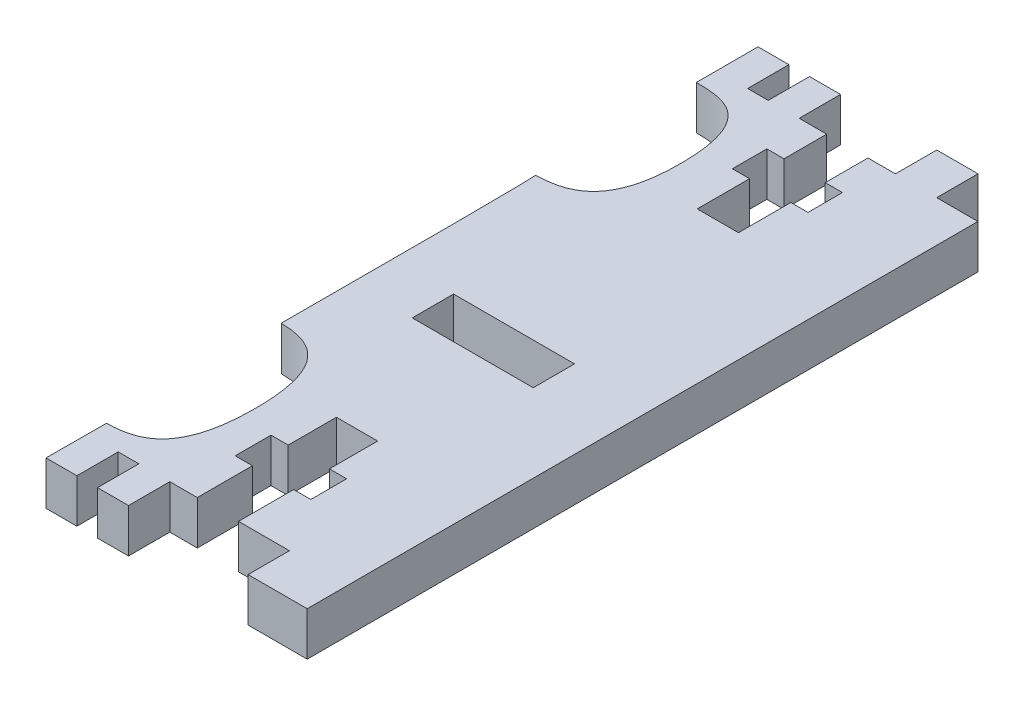
SolidWorks part; units mm, degrees
material "Acrylic (Medium-high impact)"
ref_plane "Front Plane" through (0, 0, 0) normal (0, 0, 1) x (1, 0, 0)
ref_plane "Top Plane" through (0, 0, 0) normal (0, 1, 0) x (1, 0, 0)
ref_plane "Right Plane" through (0, 0, 0) normal (1, 0, 0) x (0, 0, -1)
sketch "Sketch1" plane through (0, 0, 0) normal (0, 1, 0) x (1, 0, 0)
  line L0 (-28.6103, -11.3519) -> (-28.6103, -15.732)
  line L1 (-28.6103, 31.4899) -> (-28.6103, 35.97)
  line L2 (-28.6103, 35.97) -> (-26.3674, 35.97)
  line L3 (-12.6388, 35.97) -> (-12.6388, 32.9698)
  line L4 (-12.6388, 32.9698) -> (-9.6441, 32.9698)
  line L5 (-9.6441, 32.9698) -> (-9.6441, -15.732)
  line L6 (-9.6441, -15.732) -> (-13.9364, -15.732)
  line L7 (-24.1183, 9.369) -> (-24.1183, 6.3689)
  line L8 (-24.1183, 6.3689) -> (-15.3339, 6.3689)
  line L9 (-15.3339, 6.3689) -> (-15.3339, 9.369)
  line L10 (-15.3339, 9.369) -> (-24.1183, 9.369)
  line L11 (-22.6209, -15.732) -> (-22.6209, -12.7318)
  line L12 (-22.6209, -12.7318) -> (-20.6245, -12.7318)
  line L13 (-20.6245, -12.7318) -> (-20.6245, -8.7317)
  line L14 (-20.6245, -8.7317) -> (-21.8722, -8.7317)
  line L15 (-21.8722, -8.7317) -> (-21.8722, -8.6317)
  line L16 (-21.8722, -8.6317) -> (-21.8722, -6.1316)
  line L17 (-21.8722, -6.1316) -> (-20.6245, -6.1316)
  line L18 (-20.6245, -6.1316) -> (-20.6245, -2.6314)
  line L19 (-20.6245, -2.6314) -> (-17.63, -2.6314)
  line L20 (-17.63, -2.6314) -> (-17.63, -6.1316)
  line L21 (-17.63, -6.1316) -> (-16.3822, -6.1316)
  line L22 (-16.3822, -6.1316) -> (-16.3822, -8.6317)
  line L23 (-16.3822, -8.6317) -> (-16.3822, -8.7317)
  line L24 (-16.3822, -8.7317) -> (-17.63, -8.7317)
  line L25 (-17.63, -8.7317) -> (-17.63, -12.7318)
  line L26 (-17.63, -12.7318) -> (-13.9364, -12.7318)
  line L27 (-13.9364, -12.7318) -> (-13.9364, -15.732)
  line L28 (-15.6335, 35.97) -> (-15.6335, 32.9698)
  line L29 (-15.6335, 32.9698) -> (-17.63, 32.9698)
  line L30 (-17.63, 32.9698) -> (-17.63, 29.8697)
  line L31 (-17.63, 29.8697) -> (-16.3822, 29.8697)
  line L32 (-16.3822, 29.8697) -> (-16.3822, 27.3696)
  line L33 (-16.3822, 27.3696) -> (-17.63, 27.3696)
  line L34 (-17.63, 27.3696) -> (-17.63, 23.5694)
  line L35 (-17.63, 23.5694) -> (-20.6245, 23.5694)
  line L36 (-20.6245, 23.5694) -> (-20.6245, 27.3696)
  line L37 (-20.6245, 27.3696) -> (-21.8722, 27.3696)
  line L38 (-21.8722, 27.3696) -> (-21.8722, 29.8697)
  line L39 (-21.8722, 29.8697) -> (-20.6245, 29.8697)
  line L40 (-20.6245, 29.8697) -> (-20.6245, 32.9698)
  line L41 (-20.6245, 32.9698) -> (-22.6209, 32.9698)
  line L42 (-22.6209, 32.9698) -> (-22.6209, 35.97)
  line L43 (-22.6209, -15.732) -> (-24.87, -15.732)
  line L44 (-24.87, 35.97) -> (-24.87, 32.9698)
  line L45 (-24.87, 32.9698) -> (-26.3674, 32.9698)
  line L46 (-26.3674, 32.9698) -> (-26.3674, 35.97)
  line L47 (-26.3674, -12.7318) -> (-24.87, -12.7318)
  line L48 (-24.87, -12.7318) -> (-24.87, -15.732)
  line L50 (-26.3674, -15.732) -> (-26.3674, -12.7318)
  line L51 (-15.6335, 35.97) -> (-12.6388, 35.97)
  line L52 (-24.87, 35.97) -> (-22.6209, 35.97)
  line L53 (-26.3674, -15.732) -> (-28.6103, -15.732)
  spline S1 degree 3 poles (-28.5584, 1.2849) (-26.3154, 1.2205) (-24.0926, 0.4757) (-24.1223, -5.1439) knots 1 1 1 1 2 2 2 2
  spline S2 degree 3 poles (-24.1223, -5.1439) (-24.152, -10.7633) (-26.5537, -11.3248) (-28.6103, -11.3519) knots 2 2 2 2 3 3 3 3
  spline S3 degree 2 poles (-28.6103, -15.732) (-28.4454, 18.0276) (-28.6103, 19.812) knots 4 4 4 5 5 5
  spline S4 degree 3 poles (-28.6103, 19.812) (-26.3674, 19.8764) (-24.017, 20.6171) (-24.0797, 26.0052) knots 5 5 5 5 6 6 6 6
  spline S5 degree 3 poles (-24.0797, 26.0052) (-24.1424, 31.3932) (-26.5537, 31.4628) (-28.6103, 31.4899) knots 6 6 6 6 7 7 7 7
  point P59 (0, 0)
  point P60 (0, 0)
  point P61 (0, 0)
  point P62 (0, 0)
  point P63 (0, 0)
  point P64 (0, 0)
  point P65 (0, 0)
  point P66 (0, 0)
  point P67 (0, 0)
  point P68 (0, 0)
  point P69 (0, 0)
  point P70 (0, 0)
  point P71 (-21.2484, -8.7317)
  point P72 (-21.2484, 29.8697)
  point P73 (0, 0)
  point P74 (0, 0)
  point P75 (0, 0)
  dimension "D1" = 3.0001
  dimension "D2" = 7.0003
  dimension "D3" = 2.6001
  dimension "D4" = 3.5001
  dimension "D5" = 26.2008
  dimension "D6" = 2.9945
  dimension "D7" = 3.8003
  dimension "D8" = 2.5001
  dimension "D9" = 3.1001
  dimension "D10" = 51.7019
extrude "Boss-Extrude1" add sketch "Sketch1" along normal blind 3.175
